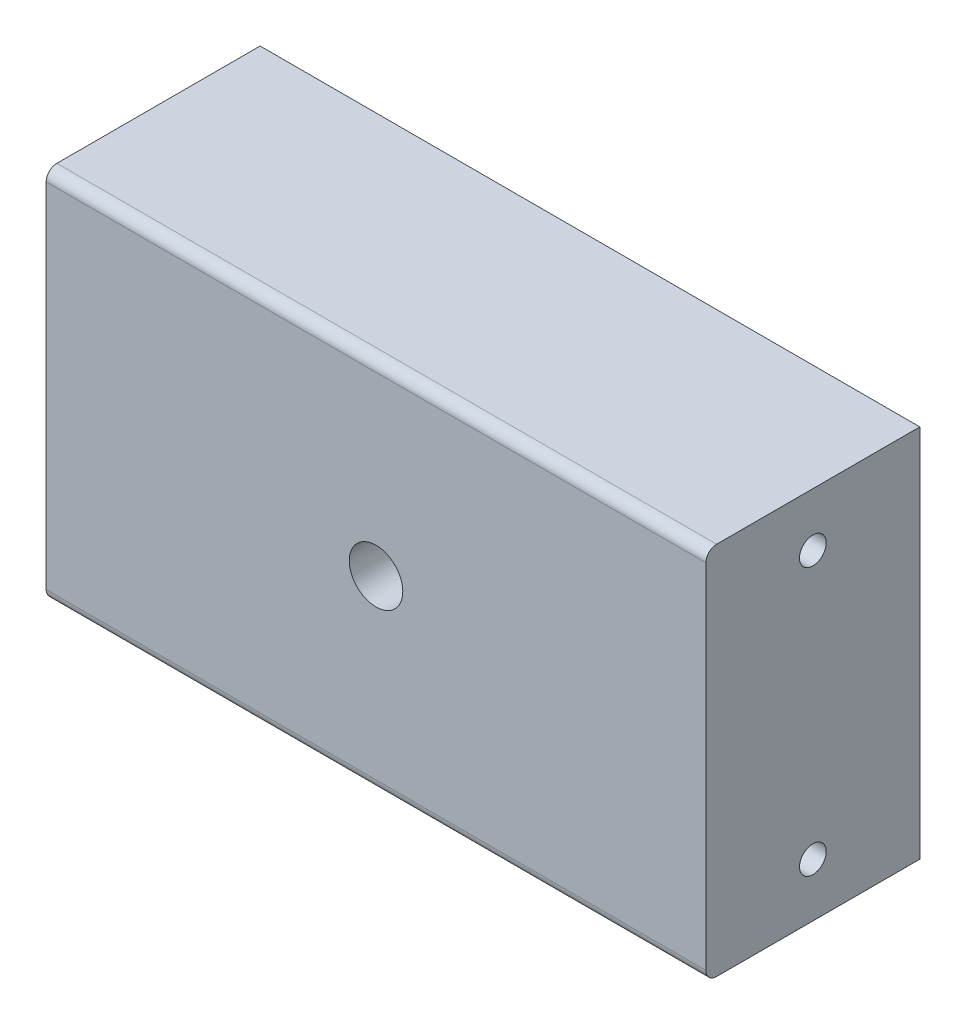
SolidWorks part; units mm, degrees
material "6061 Alloy"
ref_plane "Front Plane" through (0, 0, 0) normal (0, 0, 1) x (1, 0, 0)
ref_plane "Top Plane" through (0, 0, 0) normal (0, 1, 0) x (1, 0, 0)
ref_plane "Right Plane" through (0, 0, 0) normal (1, 0, 0) x (0, 0, -1)
sketch "Sketch2" plane through (0, 0, 0) normal (0, 0, 1) x (1, 0, 0)
  line L1 (-30.8375, 17.5) -> (30.8375, 17.5)
  line L2 (-30.8375, 17.5) -> (-30.8375, -17.5)
  line L3 (-30.8375, -17.5) -> (30.8375, -17.5)
  line L4 (30.8375, 17.5) -> (30.8375, -17.5)
  circle A0 centre (0, 0) radius 3 construction
  point P4 (0, 17.5)
  point P6 (-30.8375, 0)
  dimension "D3" = 6
  dimension "D1" = 35
  dimension "D2" = 61.675
extrude "Boss-Extrude1" add sketch "Sketch2" against normal blind 20 contours L1 L4 L3 L2
hole_wizard "Tap Drill for M6x1.0 Tap1" positions "3DSketch1" profile "Sketch3" hole size "M6x1.0" standard "ANSI Metric" end condition up to next
sketch3d "3DSketch1"
  point P0 (0, 0, 0)
sketch "Sketch3" plane through (0, 0, 0) normal (1, 0, 0) x (0, -1, 0)
  line L0 (0, 0) -> (0, 20)
  line L1 (0, 20) -> (2.5, 20)
  line L2 (2.5, 20) -> (2.5, 0)
  line L5 (2.5, 0) -> (0, 0)
  line L11 (0, -6.35) -> (0, 107.95) construction
  dimension "Thru Hole Dia." = 5
  dimension "Thru Hole Depth" = 20
sketch "Sketch4" plane through (30.8375, 0, 0) normal (1, 0, 0) x (0, 0, -1)
  line L0 (10, 12.5) -> (10, -12.5) construction
  line L4 (0, 17.5) -> (0, -17.5)
  line L5 (0, -17.5) -> (20, -17.5)
  line L6 (20, -17.5) -> (20, 17.5)
  line L7 (20, 17.5) -> (0, 17.5)
  line L8 (0, 17.5) -> (0, -17.5)
  line L9 (0, -17.5) -> (20, -17.5)
  line L10 (20, -17.5) -> (20, 17.5)
  line L11 (20, 17.5) -> (0, 17.5)
  circle A0 centre (10, 12.5) radius 1.5 construction
  circle A1 centre (10, -12.5) radius 1.5 construction
  point P8 (10, 0)
  point P9 (10, 17.5)
  dimension "D2" = 25
  dimension "D3" = 3
  dimension "D1" = 0
hole_wizard "Tap Drill for M3x0.5 Tap1" positions "3DSketch2" profile "Sketch6" hole size "M3x0.5" standard "ANSI Metric"
sketch3d "3DSketch2"
  point P0 (30.8375, 12.5, -10)
  point P2 (30.8375, -12.5, -10)
sketch "Sketch6" plane through (30.8375, 12.5, -10) normal (0, 1, 0) x (0, 0, -1)
  line L0 (0, 0) -> (0, 8.2511)
  line L1 (0, 8.2511) -> (1.25, 7.5)
  line L2 (1.25, 7.5) -> (1.25, 0)
  line L5 (1.25, 0) -> (0, 0)
  line L10 (0, 8.2511) -> (-1.25, 7.5) construction
  line L11 (0, -6.35) -> (0, 107.95) construction
  dimension "Hole Dia." = 2.5
  dimension "Hole Depth" = 7.5
  dimension "Drill Angle" = 118
mirror "Mirror1" about plane through (0, 0, 0) normal (1, 0, 0) of "Tap Drill for M3x0.5 Tap1"
fillet "Fillet1" radius 1 2 edges at (0, -17.5, 0) (0, 17.5, 0)
